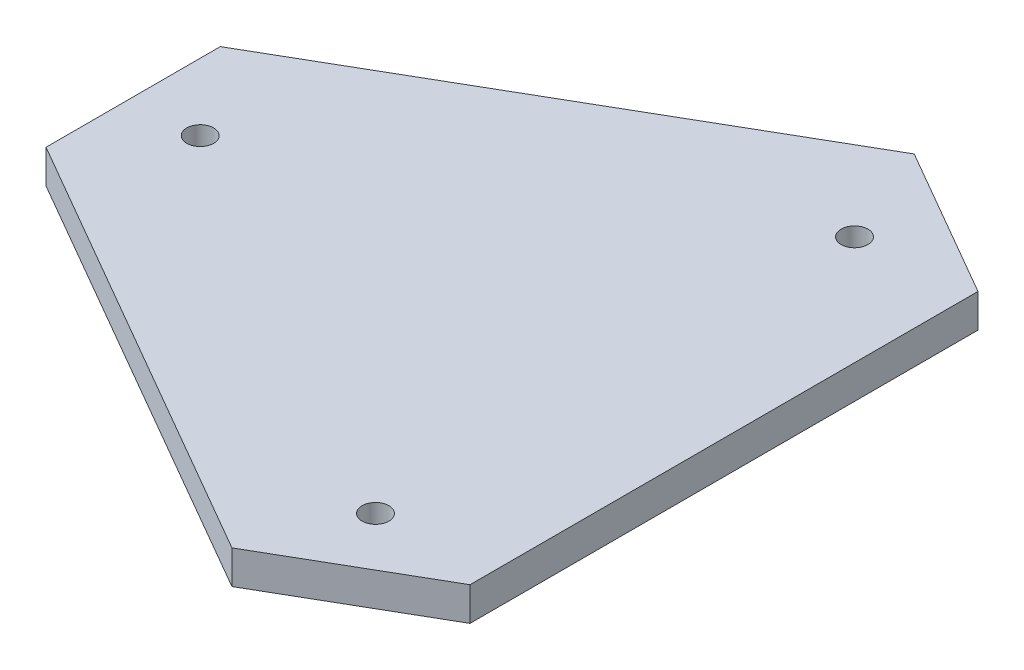
SolidWorks part; units mm, degrees
material "Acrylic (Medium-high impact)"
ref_plane "Front Plane" through (0, 0, 0) normal (0, 0, 1) x (1, 0, 0)
ref_plane "Top Plane" through (0, 0, 0) normal (0, 1, 0) x (1, 0, 0)
ref_plane "Right Plane" through (0, 0, 0) normal (1, 0, 0) x (0, 0, -1)
sketch "Sketch16" plane through (0, 0, 0) normal (0, 1, 0) x (1, 0, 0)
  line L6 (-51.252, -13) -> (-51.252, 13)
  line L7 (-51.252, 13) -> (14.3677, 50.8855)
  line L8 (14.3677, 50.8855) -> (36.8843, 37.8855)
  line L9 (36.8843, 37.8855) -> (36.8843, -37.8855)
  line L10 (36.8843, -37.8855) -> (14.3677, -50.8855)
  line L11 (14.3677, -50.8855) -> (-51.252, -13)
  circle A2 centre (0, 0) radius 52.875
  circle A3 centre (-41.252, 0) radius 2
  circle A4 centre (20.626, 35.7253) radius 2
  circle A5 centre (20.626, -35.7253) radius 2
  point P18 (0, 0)
  dimension "D6" = 105.75
  dimension "D1" = 4
  dimension "D2" = 10
  dimension "D3" = 3
  dimension "D7" = 26
extrude "Boss-Extrude1" add sketch "Sketch16" along normal blind 5 contours L11 L10 L9 L8 L7 L6 A5 A4 A3
